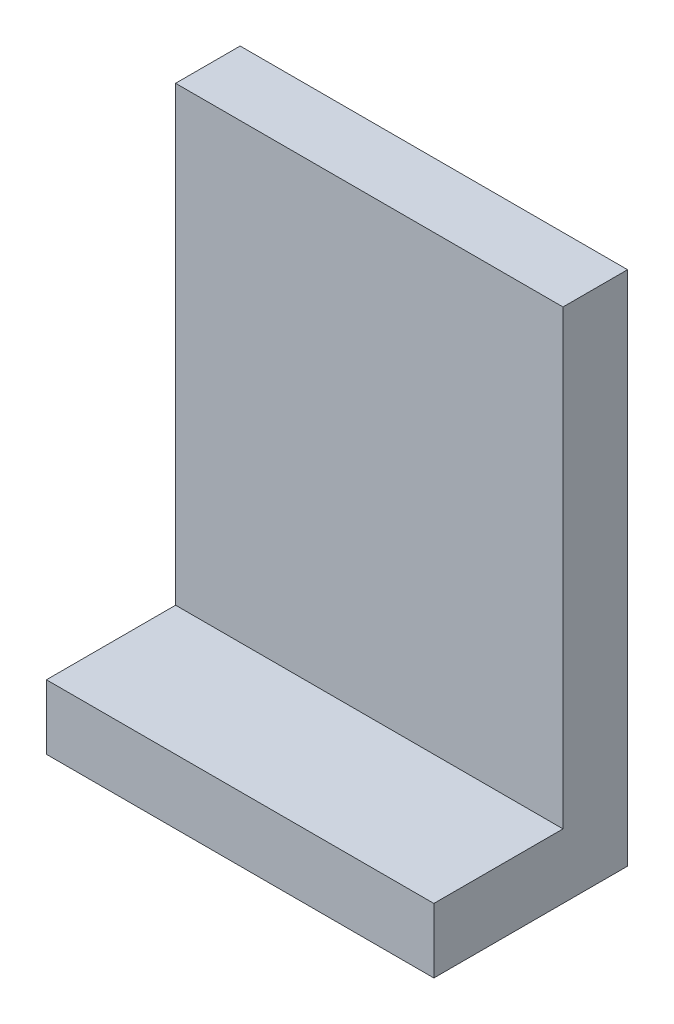
SolidWorks part; units mm, degrees
ref_plane "Plan de face" through (0, 0, 0) normal (0, 0, 1) x (1, 0, 0)
ref_plane "Plan de dessus" through (0, 0, 0) normal (0, 1, 0) x (1, 0, 0)
ref_plane "Plan de droite" through (0, 0, 0) normal (1, 0, 0) x (0, 0, -1)
sketch "Esquisse1" plane through (0, 0, 0) normal (0, 1, 0) x (1, 0, 0)
  line L0 (0, 30) -> (0, 20)
  line L1 (0, 0) -> (60, 0)
  line L2 (0, 0) -> (0, 30)
  line L3 (0, 30) -> (60, 30)
  line L4 (60, 0) -> (60, 30)
  line L5 (0, 20) -> (60, 20)
  dimension "D1" = 30
  dimension "D2" = 60
extrude "Boss.-Extru.1" add sketch "Esquisse1" along normal blind 10 contours L5 L2 L1 L4 | L0 L5 L4 L3
sketch "Esquisse2" plane through (0, 10, 0) normal (0, 1, 0) x (1, 0, 0)
  line L0 (60, 30) -> (60, 20)
  line L1 (60, 0) -> (60, 30) construction
  line L2 (60, 20) -> (0, 20)
  line L3 (0, 0) -> (0, 30) construction
  line L4 (0, 20) -> (0, 30)
  line L5 (0, 30) -> (60, 30)
extrude "Boss.-Extru.2" add sketch "Esquisse2" along normal blind 70
